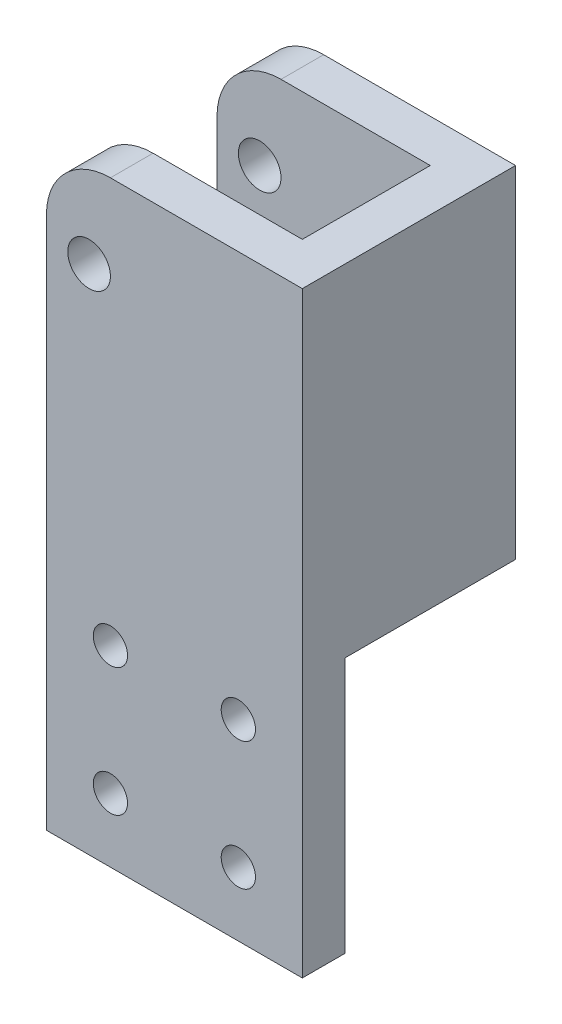
SolidWorks part; units mm, degrees
material "6061-T6 (SS)"
ref_plane "Front Plane" through (0, 0, 0) normal (0, 0, 1) x (1, 0, 0)
ref_plane "Top Plane" through (0, 0, 0) normal (0, 1, 0) x (1, 0, 0)
ref_plane "Right Plane" through (0, 0, 0) normal (1, 0, 0) x (0, 0, -1)
sketch "Sketch1" plane through (0, 0, 0) normal (0, 0, 1) x (1, 0, 0)
  line L1 (0, 0) -> (38.1, 0)
  line L2 (0, 0) -> (0, 76.2)
  line L3 (0, 76.2) -> (38.1, 76.2)
  line L4 (38.1, 0) -> (38.1, 76.2)
  dimension "D1" = 76.2
  dimension "D2" = 38.1
extrude "Boss-Extrude1" add sketch "Sketch1" against normal blind 31.75
sketch "Sketch2" plane through (0, 76.2, 0) normal (0, 1, 0) x (1, 0, 0)
  line L0 (0, 0) -> (0, 6.35)
  line L1 (0, 31.75) -> (0, 0) construction
  line L2 (0, 6.35) -> (31.75, 6.35)
  line L3 (31.75, 6.35) -> (31.75, 31.75)
  line L4 (38.1, 31.75) -> (0, 31.75) construction
  line L5 (38.1, 31.75) -> (38.1, 0) construction
  line L6 (31.75, 6.35) -> (31.75, 25.4) construction
  dimension "D1" = 6.35
  dimension "D2" = 6.35
  dimension "D3" = 19.05
sketch "Sketch3" plane through (0, 0, 0) normal (-1, 0, 0) x (0, 0, 1)
  line L0 (-31.75, 0) -> (-6.35, 0)
  line L1 (-31.75, 0) -> (0, 0) construction
  line L4 (-31.75, 0) -> (-31.75, 76.2)
  line L5 (-31.75, 76.2) -> (-6.35, 76.2)
  line L6 (-6.35, 0) -> (-6.35, 76.2)
  dimension "D1" = 25.4
  dimension "D2" = 76.2
extrude "Cut-Extrude2" cut sketch "Sketch3" against normal blind 31.75
sketch "Sketch4" plane through (31.75, 0, 0) normal (-1, 0, 0) x (0, 0, 1)
  line L0 (-6.35, 0) -> (-6.35, 76.2) construction
  line L1 (-31.75, 0) -> (-6.35, 0)
  line L2 (-31.75, 0) -> (-31.75, 25.4)
  line L3 (-31.75, 25.4) -> (-6.35, 25.4)
  line L4 (-6.35, 0) -> (-6.35, 25.4)
  dimension "D1" = 25.4
extrude "Cut-Extrude3" cut sketch "Sketch4" against normal through all
sketch "Sketch5" plane through (0, 76.2, 0) normal (0, 1, 0) x (1, 0, 0)
  line L0 (38.1, 31.75) -> (38.1, 0) construction
  line L1 (38.1, 0) -> (0, 0) construction
  line L2 (0, 0) -> (0, 6.35) construction
  line L3 (0, 6.35) -> (31.75, 6.35) construction
  line L4 (31.75, 6.35) -> (31.75, 31.75) construction
  line L5 (31.75, 31.75) -> (38.1, 31.75) construction
  line L6 (31.75, 6.35) -> (31.75, 25.4)
  line L7 (31.75, 31.75) -> (0, 31.75)
  line L8 (0, 31.75) -> (0, 25.4)
  line L9 (0, 25.4) -> (31.75, 25.4)
  line M6 (31.75, 31.75) -> (31.75, 6.35)
  dimension "D1" = 19.05
extrude "Boss-Extrude2" add sketch "Sketch5" against normal blind 50.8 contours L8 L9 L7 M6
sketch "Sketch6" plane through (0, 0, -31.75) normal (0, 0, -1) x (-1, 0, 0)
  line L0 (0, 76.2) -> (0, 63.5) construction
  line L1 (0, 25.4) -> (0, 76.2) construction
  line L2 (0, 63.5) -> (-6.35, 63.5) construction
  circle A0 centre (-6.35, 63.5) radius 3.175
  dimension "D3" = 6.35
  dimension "D1" = 12.7
  dimension "D2" = 6.35
extrude "Cut-Extrude4" cut sketch "Sketch6" against normal blind 50.8
fillet "Fillet2" radius 9.525 2 edges at (0, 76.2, -3.175) (0, 76.2, -28.575)
ref_plane "Plane1" through (0, 25.4, 0) normal (0, -1, 0) x (-1, 0, 0)
sketch "Sketch7" plane through (0, 25.4, 0) normal (0, -1, 0) x (-1, 0, 0)
  line L1 (0, 25.4) -> (-31.75, 25.4)
  line L2 (0, 25.4) -> (0, 6.35)
  line L3 (0, 6.35) -> (-31.75, 6.35)
  line L4 (-31.75, 25.4) -> (-31.75, 6.35)
extrude "Boss-Extrude3" add sketch "Sketch7" against normal blind 6.35
sketch "Sketch11" plane through (0, 0, 0) normal (0, -1, 0) x (1, 0, 0)
  line L1 (0, -6.35) -> (38.1, -6.35)
  line L2 (0, -6.35) -> (0, 0)
  line L3 (0, 0) -> (38.1, 0)
  line L4 (38.1, -6.35) -> (38.1, 0)
extrude "Boss-Extrude4" add sketch "Sketch11" along normal blind 12.7
sketch "Sketch8" plane through (0, 0, 0) normal (0, 0, 1) x (1, 0, 0)
  line L0 (0, -12.7) -> (0, 25.4) construction
  line L1 (0, 66.675) -> (0, -12.7) construction
  line L2 (0, 25.4) -> (38.1, 25.4) construction
  line L3 (38.1, -12.7) -> (38.1, 76.2) construction
  line L4 (38.1, 25.4) -> (38.1, -12.7) construction
  line L5 (38.1, -12.7) -> (0, -12.7) construction
  point P0 (9.525, 15.875)
  point P1 (28.575, 15.875)
  point P28 (9.525, -3.175)
  point P33 (28.575, -3.175)
  dimension "D4" = 9.525
  dimension "D5" = 9.525
  dimension "D6" = 9.525
  dimension "D1" = 38.1
  dimension "D2" = 9.525
  dimension "D3" = 9.525
  dimension "D7" = 9.525
  dimension "D8" = 9.525
  dimension "D9" = 9.525
hole_wizard "1/4-20 Tapped Hole2" positions "3DSketch2" profile "Sketch10" tap size "1/4-20" standard "ANSI Inch"
sketch3d "3DSketch2"
  point P9 (9.525, -3.175, 0)
  point P12 (28.575, -3.175, 0)
  point P19 (9.525, 15.875, 0)
  point P22 (28.575, 15.875, 0)
sketch "Sketch10" plane through (9.525, -3.175, 0) normal (1, 0, 0) x (0, -1, 0)
  line L0 (0, 0) -> (0, 18.0438)
  line L1 (0, 18.0438) -> (2.5527, 16.51)
  line L2 (2.5527, 16.51) -> (2.5527, 0)
  line L5 (2.5527, 0) -> (0, 0)
  line L10 (0, 18.0438) -> (-2.5527, 16.51) construction
  line L11 (0, -6.35) -> (0, 107.95) construction
  dimension "Tap Drill Dia." = 5.1054
  dimension "Tap Drill Depth" = 16.51
  dimension "Drill Angle" = 118
